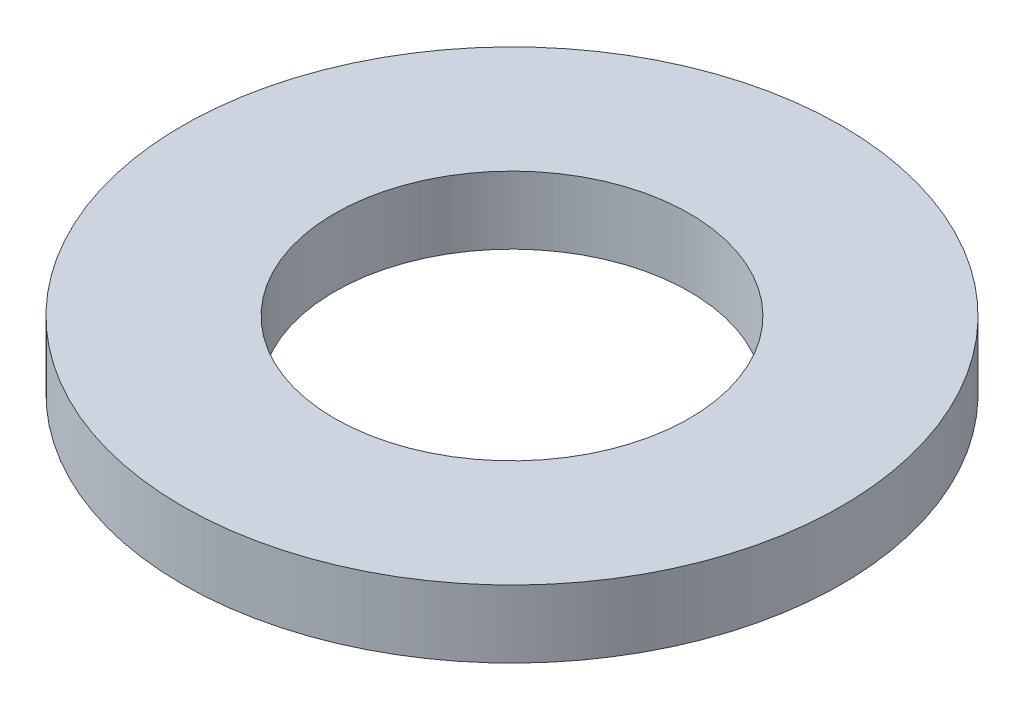
SolidWorks part; units mm, degrees
ref_plane "Front Plane" through (0, 0, 0) normal (0, 0, 1) x (1, 0, 0)
ref_plane "Top Plane" through (0, 0, 0) normal (0, 1, 0) x (1, 0, 0)
ref_plane "Right Plane" through (0, 0, 0) normal (1, 0, 0) x (0, 0, -1)
sketch "Sketch1" plane through (0, 0, 0) normal (0, 1, 0) x (1, 0, 0)
  circle A0 centre (0, 0) radius 4.875
  circle A1 centre (0, 0) radius 2.625
  dimension "D1" = 5.25
  dimension "D2" = 9.75
extrude "Boss-Extrude1" add sketch "Sketch1" along normal blind 1
